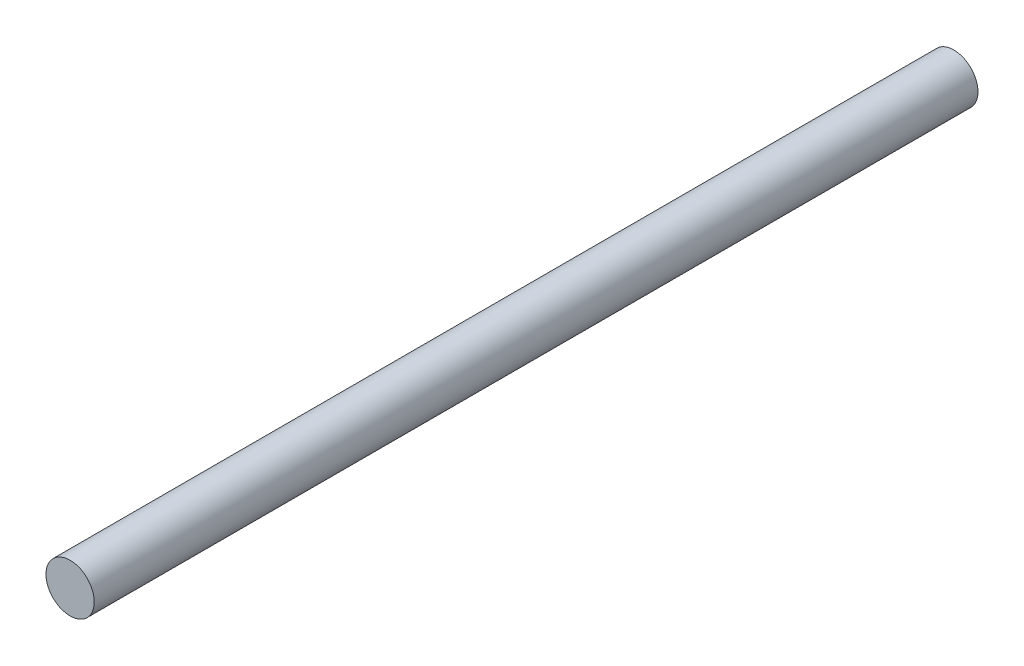
SolidWorks part; units mm, degrees
ref_plane "Plan de face" through (0, 0, 0) normal (0, 0, 1) x (1, 0, 0)
ref_plane "Plan de dessus" through (0, 0, 0) normal (0, 1, 0) x (1, 0, 0)
ref_plane "Plan de droite" through (0, 0, 0) normal (1, 0, 0) x (0, 0, -1)
sketch "Esquisse1" plane through (0, 0, 0) normal (0, 0, 1) x (1, 0, 0)
  circle A0 centre (0, 0) radius 2.95
  dimension "D1" = 5.9
extrude "Boss.-Extru.1" add sketch "Esquisse1" along normal blind 108
